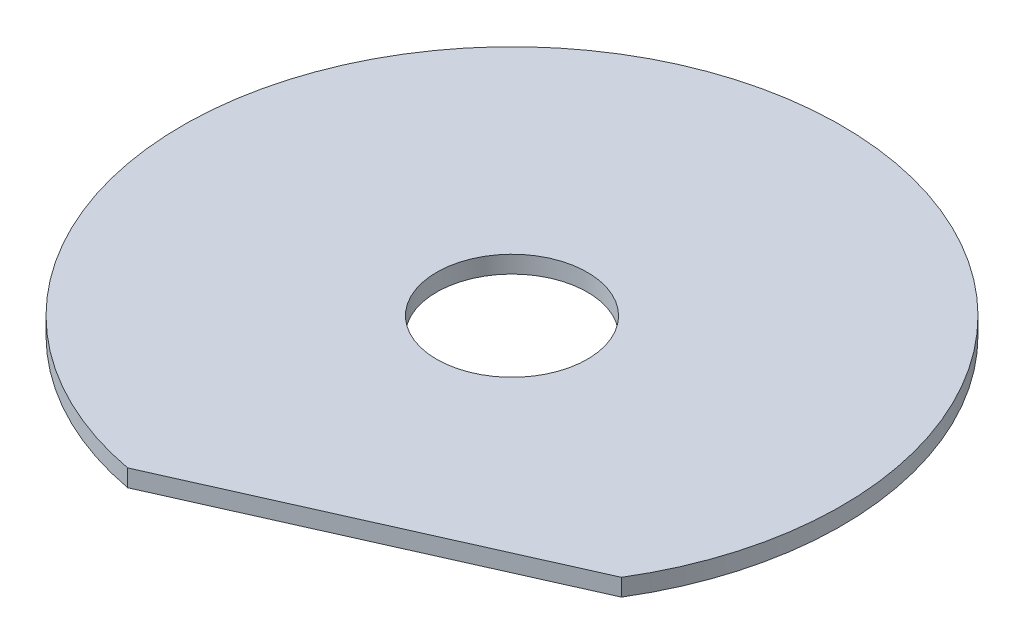
SolidWorks part; units mm, degrees
material "AISI 316 Stainless Steel Sheet (SS)"
ref_plane "Front Plane" through (0, 0, 0) normal (0, 0, 1) x (1, 0, 0)
ref_plane "Top Plane" through (0, 0, 0) normal (0, 1, 0) x (1, 0, 0)
ref_plane "Right Plane" through (0, 0, 0) normal (1, 0, 0) x (0, 0, -1)
sketch "Sketch5" plane through (0, 0, 0) normal (0, 1, 0) x (1, 0, 0)
  circle A0 centre (0, 0) radius 18.9865
extrude "Boss-Extrude3" add sketch "Sketch5" along normal blind 0.9906
sketch "Sketch6" plane through (0, 0.9906, 0) normal (0, 1, 0) x (1, 0, 0)
  circle A0 centre (0, 0) radius 4.3434
extrude "Cut-Extrude2" cut sketch "Sketch6" against normal through all
sketch "Sketch7" plane through (0, 0.9906, 0) normal (0, 1, 0) x (1, 0, 0)
  line L0 (-3.4821, -18.6645) -> (16.2019, -9.8987)
  circle A0 centre (0, 0) radius 18.9865 construction
  arc A1 (-3.4821, -18.6645) -> (16.2019, -9.8987) centre (0, 0) ccw
  dimension "D1" = 34.6202
extrude "Cut-Extrude3" cut sketch "Sketch7" against normal through all
ref_plane "mid plane" through (0, 0.508, 0) normal (0, 1, 0) x (1, 0, 0)
